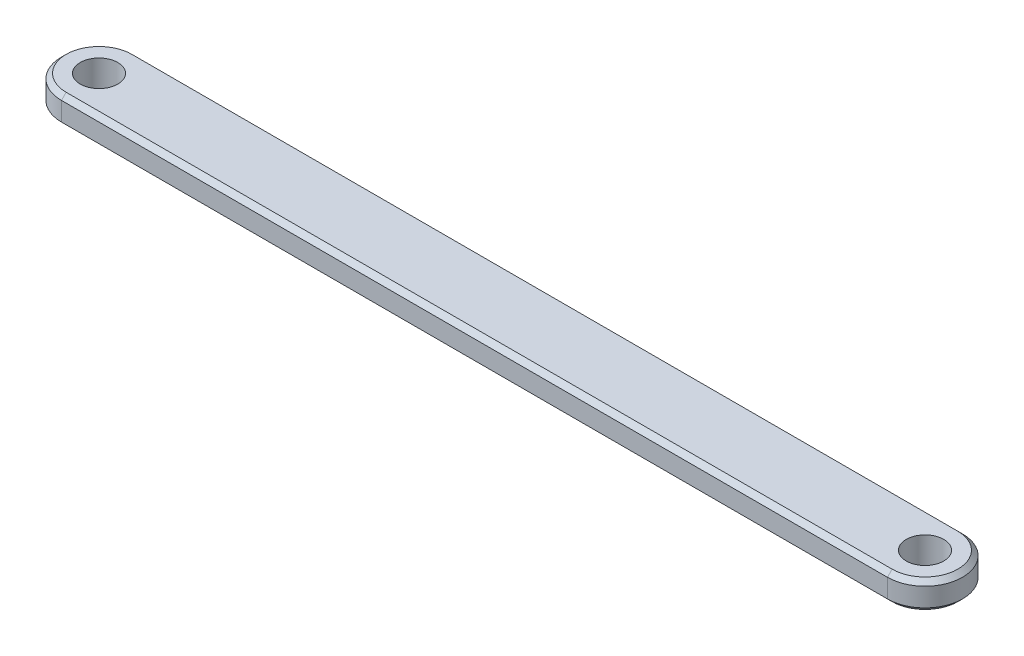
SolidWorks part; units mm, degrees
material "AISI 1020 Steel, Cold Rolled"
ref_plane "Front Plane" through (0, 0, 0) normal (0, 0, 1) x (1, 0, 0)
ref_plane "Top Plane" through (0, 0, 0) normal (0, 1, 0) x (1, 0, 0)
ref_plane "Right Plane" through (0, 0, 0) normal (1, 0, 0) x (0, 0, -1)
sketch "Sketch1" plane through (0, 0, 0) normal (0, 1, 0) x (1, 0, 0)
  line L0 (0, 0) -> (88, 0) construction
  line L1 (0, 4) -> (88, 4)
  line L2 (0, -4) -> (88, -4)
  arc A0 (0, 4) -> (0, -4) centre (0, 0) ccw
  arc A1 (88, -4) -> (88, 4) centre (88, 0) ccw
  circle A2 centre (0, 0) radius 2
  circle A3 centre (88, 0) radius 2
  point P3 (44, 0)
  dimension "D2" = 4
  dimension "D3" = 4
  dimension "D1" = 88
extrude "Boss-Extrude1" add sketch "Sketch1" along normal mid plane 3
chamfer "Chamfer1" distance 0.5 angle 45 8 edges at (44, -1.5, -4) (-4, -1.5, 0) (92, -1.5, 0) (44, -1.5, 4) (-4, 1.5, 0) (44, 1.5, 4) (44, 1.5, -4) (92, 1.5, 0)
